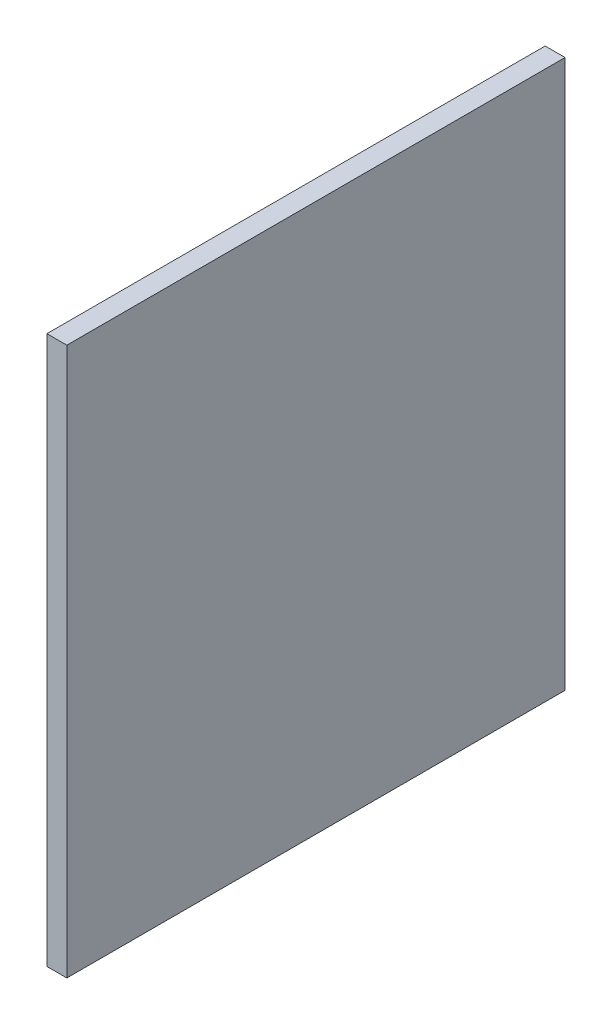
SolidWorks part; units mm, degrees
ref_plane "Front Plane" through (0, 0, 0) normal (0, 0, 1) x (1, 0, 0)
ref_plane "Top Plane" through (0, 0, 0) normal (0, 1, 0) x (1, 0, 0)
ref_plane "Right Plane" through (0, 0, 0) normal (1, 0, 0) x (0, 0, -1)
sketch "Sketch1" plane through (0, 0, 0) normal (1, 0, 0) x (0, 0, -1)
  line L1 (25, -27.5) -> (-25, -27.5)
  line L2 (25, -27.5) -> (25, 27.5)
  line L3 (25, 27.5) -> (-25, 27.5)
  line L4 (-25, -27.5) -> (-25, 27.5)
  line L5 (25, -27.5) -> (-25, 27.5) construction
  line L6 (25, 27.5) -> (-25, -27.5) construction
  point P0 (0, 0)
  dimension "D1" = 50
  dimension "D2" = 55
extrude "Boss-Extrude1" add sketch "Sketch1" along normal blind 2
